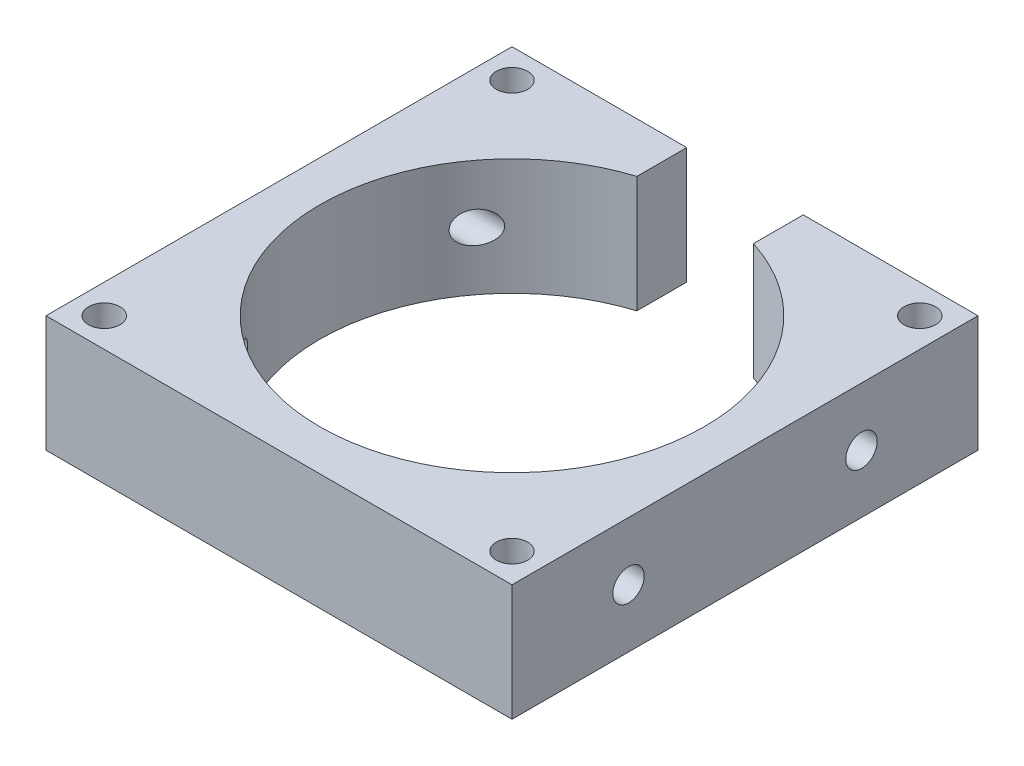
SolidWorks part; units mm, degrees
ref_plane "Front Plane" through (0, 0, 0) normal (0, 0, 1) x (1, 0, 0)
ref_plane "Top Plane" through (0, 0, 0) normal (0, 1, 0) x (1, 0, 0)
ref_plane "Right Plane" through (0, 0, 0) normal (1, 0, 0) x (0, 0, -1)
sketch "Sketch1" plane through (0, 0, 0) normal (0, 1, 0) x (1, 0, 0)
  line L1 (-50.8, -50.8) -> (50.8, -50.8)
  line L2 (-50.8, -50.8) -> (-50.8, 50.8)
  line L3 (-50.8, 50.8) -> (50.8, 50.8)
  line L4 (50.8, -50.8) -> (50.8, 50.8)
  line L5 (-50.8, -50.8) -> (50.8, 50.8) construction
  line L6 (-50.8, 50.8) -> (50.8, -50.8) construction
  point P0 (0, 0)
  dimension "D1" = 101.6
  dimension "D2" = 101.6
extrude "Boss-Extrude1" add sketch "Sketch1" along normal blind 25.4
sketch "Sketch2" plane through (0, 25.4, 0) normal (0, 1, 0) x (1, 0, 0)
  circle A0 centre (0, 0) radius 41.91
  dimension "D1" = 83.82
extrude "Cut-Extrude1" cut sketch "Sketch2" against normal through all
sketch "Sketch3" plane through (0, 0, 0) normal (0, 1, 0) x (1, 0, 0)
  line L0 (50.8, 50.8) -> (-50.8, 50.8) construction
  line L1 (12.7, 68.132) -> (-12.7, 68.132)
  line L2 (12.7, 68.132) -> (12.7, 33.468)
  line L3 (12.7, 33.468) -> (-12.7, 33.468)
  line L4 (-12.7, 68.132) -> (-12.7, 33.468)
  line L5 (12.7, 68.132) -> (-12.7, 33.468) construction
  line L6 (12.7, 33.468) -> (-12.7, 68.132) construction
  point P0 (0, 50.8)
  dimension "D1" = 25.4
extrude "Cut-Extrude2" cut sketch "Sketch3" along normal through all
sketch "Sketch4" plane through (0, 25.4, 0) normal (0, 1, 0) x (1, 0, 0)
  line L0 (-12.7, 50.8) -> (-50.8, 50.8) construction
  line L1 (-50.8, 50.8) -> (-50.8, -50.8) construction
  circle A0 centre (-44.45, 44.45) radius 3.429
  circle A1 centre (44.45, 44.45) radius 3.429
  circle A2 centre (44.45, -44.45) radius 3.429
  circle A3 centre (-44.45, -44.45) radius 3.429
  dimension "D1" = 6.858
  dimension "D2" = 6.35
  dimension "D3" = 6.35
  dimension "D6" = 88.9
  dimension "D7" = 88.9
  dimension "D4" = 2
  dimension "D5" = 2
extrude "Cut-Extrude3" cut sketch "Sketch4" against normal through all
sketch "Sketch5" plane through (-50.8, 0, 0) normal (-1, 0, 0) x (0, 0, 1)
  line L0 (-50.8, 12.7) -> (50.8, 12.7) construction
  line L1 (-50.8, 25.4) -> (-50.8, 0) construction
  line L2 (50.8, 25.4) -> (50.8, 0) construction
  circle A0 centre (-25.4, 12.7) radius 3.429
  circle A1 centre (25.4, 12.7) radius 3.429
  point P10 (0, 0)
  point P11 (0, 0)
  point P12 (0, 12.7)
  dimension "D1" = 50.8
  dimension "D2" = 6.858
  dimension "D3" = 25.4
extrude "Cut-Extrude4" cut sketch "Sketch5" against normal through all
